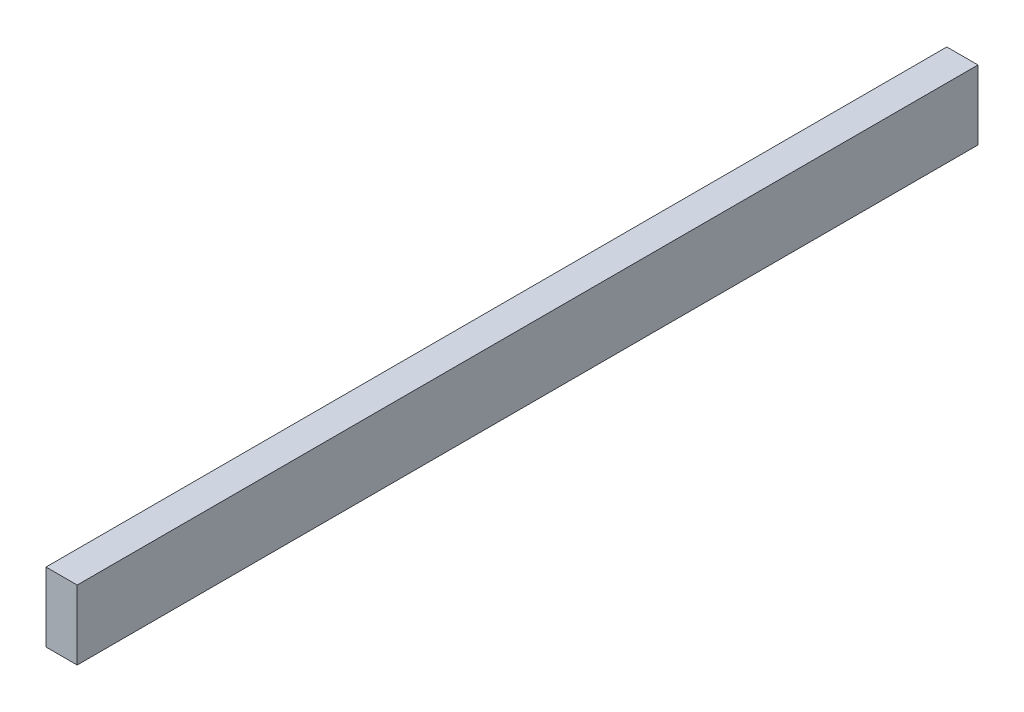
SolidWorks part; units mm, degrees
ref_plane "Plan de face" through (0, 0, 0) normal (0, 0, 1) x (1, 0, 0)
ref_plane "Plan de dessus" through (0, 0, 0) normal (0, 1, 0) x (1, 0, 0)
ref_plane "Plan de droite" through (0, 0, 0) normal (1, 0, 0) x (0, 0, -1)
sketch "Esquisse1" plane through (0, 0, 0) normal (0, 0, 1) x (1, 0, 0)
  line L1 (0, 0) -> (27, 0)
  line L2 (0, 0) -> (0, 60)
  line L3 (0, 60) -> (27, 60)
  line L4 (27, 0) -> (27, 60)
  dimension "D1" = 27
  dimension "D2" = 60
extrude "Boss.-Extru.1" add sketch "Esquisse1" along normal blind 780
